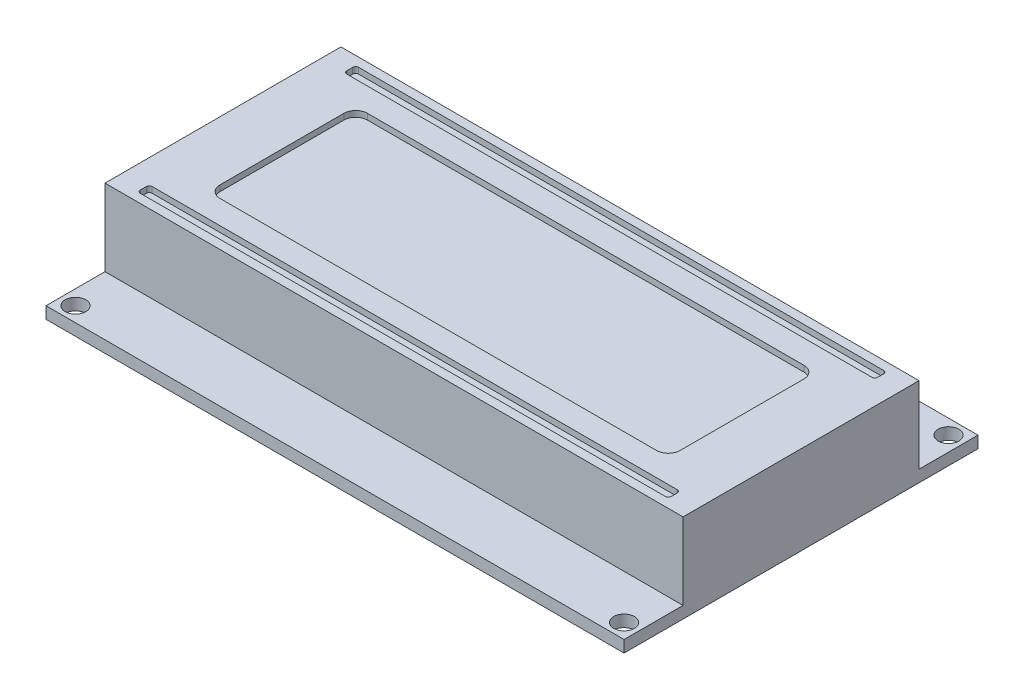
SolidWorks part; units mm, degrees
ref_plane "Front Plane" through (0, 0, 0) normal (0, 0, 1) x (1, 0, 0)
ref_plane "Top Plane" through (0, 0, 0) normal (0, 1, 0) x (1, 0, 0)
ref_plane "Right Plane" through (0, 0, 0) normal (1, 0, 0) x (0, 0, -1)
sketch "Sketch1" plane through (0, 0, 0) normal (0, 1, 0) x (1, 0, 0)
  line L0 (75, 55) -> (75, 0) construction
  line L1 (0, 0) -> (150, 0)
  line L2 (0, 0) -> (0, 55)
  line L3 (0, 55) -> (150, 55)
  line L4 (150, 0) -> (150, 55)
  line L5 (0, 27.5) -> (150, 27.5) construction
  circle A0 centre (3, 52) radius 1.5
  circle A1 centre (147, 52) radius 1.5
  circle A2 centre (147, 3) radius 1.5
  circle A3 centre (3, 3) radius 1.5
  dimension "D3" = 3
  dimension "D1" = 55
  dimension "D2" = 150
  dimension "D4" = 3
  dimension "D5" = 3
extrude "Boss-Extrude1" add sketch "Sketch1" along normal blind 2
sketch "Sketch2" plane through (0, 2, 0) normal (0, 1, 0) x (1, 0, 0)
  line L0 (0, 0) -> (150, 0) construction
  line L1 (0, 0) -> (0, 55) construction
  circle A0 centre (13, 10) radius 6
  dimension "D1" = 12
  dimension "D2" = 10
  dimension "D3" = 13
extrude "Boss-Extrude2" add sketch "Sketch2" along normal blind 10
sketch "Sketch3" plane through (0, 2, 0) normal (0, 1, 0) x (1, 0, 0)
  line L0 (0, 27.5) -> (150, 27.5) construction
  line L1 (7, 33.5) -> (19, 33.5)
  line L2 (7, 33.5) -> (7, 21.5)
  line L3 (7, 21.5) -> (19, 21.5)
  line L4 (19, 33.5) -> (19, 21.5)
  line L5 (13, 0) -> (13, 55) construction
  line L6 (0, 0) -> (150, 0) construction
  line L7 (0, 55) -> (150, 55) construction
  line L8 (7, 27.5) -> (19, 27.5) construction
  circle A1 centre (13, 10) radius 6 construction
  point P4 (7, 27.5)
  point P16 (13, 27.5)
  point P19 (13, 16)
  dimension "D1" = 12
  dimension "D2" = 12
extrude "Boss-Extrude3" add sketch "Sketch3" along normal blind 25
sketch "Sketch4" plane through (0, 2, 0) normal (0, 1, 0) x (1, 0, 0)
  line L0 (13, 45.5) -> (13, 40.5) construction
  line L1 (10.5, 45.5) -> (15.5, 45.5)
  line L2 (10.5, 45.5) -> (10.5, 40.5)
  line L3 (10.5, 40.5) -> (15.5, 40.5)
  line L4 (15.5, 45.5) -> (15.5, 40.5)
  line L5 (10.5, 43) -> (15.5, 43) construction
  line L7 (13, 0) -> (13, 55) construction
  line L8 (7, 33.5) -> (19, 33.5) construction
  line L9 (150, 0) -> (150, 55) construction
  line L10 (127, 8) -> (86, 8)
  line L11 (127, 8) -> (127, 5)
  line L12 (127, 5) -> (86, 5)
  line L13 (86, 8) -> (86, 5)
  line L14 (0, 0) -> (150, 0) construction
  point P8 (13, 43)
  dimension "D1" = 5
  dimension "D2" = 5
  dimension "D3" = 7
  dimension "D4" = 23
  dimension "D5" = 41
  dimension "D6" = 3
  dimension "D7" = 5
extrude "Boss-Extrude4" add sketch "Sketch4" along normal blind 5
sketch "Sketch5" plane through (0, 7, 0) normal (0, 1, 0) x (1, 0, 0)
  line L0 (86, 5) -> (127, 5) construction
  line L1 (86, 8) -> (127, 8)
  line L2 (86, 8) -> (86, 5)
  line L3 (86, 5) -> (127, 5)
  line L4 (127, 8) -> (127, 5)
  line L5 (86, 5) -> (127, 5) construction
  line L6 (10.5, 43) -> (15.5, 43) construction
  line L7 (10.5, 45.5) -> (10.5, 40.5) construction
  line L8 (15.5, 40.5) -> (15.5, 45.5) construction
  line L10 (10.5, 45.5) -> (15.5, 45.5)
  line L11 (10.5, 45.5) -> (10.5, 40.5)
  line L12 (10.5, 40.5) -> (15.5, 40.5)
  line L13 (15.5, 45.5) -> (15.5, 40.5)
  circle A0 centre (13, 43) radius 1.5
  point P15 (13, 43)
  dimension "D1" = 3
extrude "Cut-Extrude1" cut sketch "Sketch5" against normal blind 2
sketch "Sketch6" plane through (0, 27, 0) normal (0, 1, 0) x (1, 0, 0)
  line L0 (10.3706, 26.0556) -> (15.6294, 26.0556)
  line L1 (7, 33.5) -> (19, 33.5)
  line L2 (7, 33.5) -> (7, 21.5)
  line L3 (7, 21.5) -> (19, 21.5)
  line L4 (19, 33.5) -> (19, 21.5)
  arc A0 (15.6294, 26.0556) -> (10.3706, 26.0556) centre (13, 27.5) ccw
  dimension "D1" = 6
extrude "Cut-Extrude2" cut sketch "Sketch6" against normal blind 13
sketch "Sketch7" plane through (0, 14, 0) normal (0, 1, 0) x (1, 0, 0)
  line L1 (7, 33.5) -> (19, 33.5)
  line L2 (7, 33.5) -> (7, 21.5)
  line L3 (7, 21.5) -> (19, 21.5)
  line L4 (19, 33.5) -> (19, 21.5)
  circle A0 centre (13, 27.5) radius 3.5
  line M4 (7, 33.5) -> (7, 21.5)
  line M5 (7, 21.5) -> (19, 21.5)
  line M6 (19, 21.5) -> (19, 33.5)
  line M7 (19, 33.5) -> (7, 33.5)
  dimension "D1" = 7
extrude "Cut-Extrude3" cut sketch "Sketch7" against normal blind 7 contours A0 M7 M4 M5 M6
sketch "Sketch8" plane through (0, 12, 0) normal (0, 1, 0) x (1, 0, 0)
  circle A0 centre (13, 10) radius 1.25
  point P0 (13, 10)
  dimension "D1" = 2.5
extrude "Cut-Extrude4" cut sketch "Sketch8" against normal blind 5
sketch "Sketch9" plane through (0, 0, 0) normal (0, -1, 0) x (1, 0, 0)
  line L0 (0, -55) -> (150, -55) construction
  line L1 (149, -20) -> (131, -20)
  line L2 (149, -20) -> (149, -47)
  line L3 (149, -47) -> (124, -47)
  line L4 (124, -22) -> (124, -47)
  line L5 (150, 0) -> (150, -55) construction
  line L6 (124, -22) -> (129, -22)
  line L7 (129, -22) -> (131, -20)
  dimension "D1" = 8
  dimension "D2" = 27
  dimension "D3" = 1
  dimension "D4" = 25
  dimension "D5" = 2
  dimension "D6" = 5
  dimension "D7" = 45
extrude "Boss-Extrude5" add sketch "Sketch9" along normal blind 3
sketch "Sketch10" plane through (149, 0, 0) normal (1, 0, 0) x (0, 0, -1)
  line L0 (20, -1.5) -> (47, -1.5) construction
  line L1 (20, -3) -> (20, 0) construction
  line L2 (47, -3) -> (47, 0) construction
  line L3 (33.5, -3) -> (33.5, 0) construction
  line L4 (47, -3) -> (20, -3) construction
  line L5 (0, 0) -> (55, 0) construction
  line L6 (33.5, -2.25) -> (33.5, -0.75) construction
  line L7 (21, -2.25) -> (46, -2.25)
  line L8 (21, -2.25) -> (21, -0.75)
  line L9 (21, -0.75) -> (46, -0.75)
  line L10 (46, -2.25) -> (46, -0.75)
  line L11 (21, -1.5) -> (46, -1.5) construction
  point P20 (33.5, -1.5)
  point P21 (33.5, -1.5)
  dimension "D1" = 1.5
  dimension "D2" = 25
extrude "Cut-Extrude5" cut sketch "Sketch10" against normal blind 18
sketch "Sketch11" plane through (0, 5, 0) normal (0, 1, 0) x (1, 0, 0)
  line L0 (0, 0) -> (150, 0) construction
  line L1 (136, 64) -> (38, 64)
  line L2 (136, 64) -> (136, 4)
  line L3 (136, 4) -> (38, 4)
  line L4 (38, 64) -> (38, 4)
  line L5 (150, 0) -> (150, 55) construction
  line L6 (87, 64) -> (87, 4) construction
  line L7 (38, 34) -> (136, 34) construction
  circle A0 centre (40.5, 61.5) radius 1.75
  circle A1 centre (133.5, 61.5) radius 1.75
  circle A2 centre (133.5, 6.5) radius 1.75
  circle A3 centre (40.5, 6.5) radius 1.75
  point P12 (87, 34)
  dimension "D5" = 3.5
  dimension "D1" = 98
  dimension "D2" = 60
  dimension "D3" = 4
  dimension "D4" = 14
  dimension "D6" = 2.5
  dimension "D7" = 2.5
extrude "Boss-Extrude6" add sketch "Sketch11" along normal blind 2
sketch "Sketch12" plane through (0, 7, 0) normal (0, 1, 0) x (1, 0, 0)
  line L0 (38, 34) -> (136, 34) construction
  line L1 (38, 54) -> (136, 54)
  line L2 (38, 54) -> (38, 14)
  line L3 (38, 14) -> (136, 14)
  line L4 (136, 54) -> (136, 14)
  dimension "D1" = 40
extrude "Boss-Extrude7" add sketch "Sketch12" along normal blind 13
sketch "Sketch13" plane through (0, 20, 0) normal (0, 1, 0) x (1, 0, 0)
  line L0 (87, 54) -> (87, 14) construction
  line L1 (136, 54) -> (38, 54) construction
  line L2 (38, 14) -> (136, 14) construction
  line L3 (38, 34) -> (136, 34) construction
  line L4 (38, 54) -> (38, 14) construction
  line L5 (136, 14) -> (136, 54) construction
  line L6 (87, 46.5) -> (87, 21.5) construction
  line L7 (50, 46.5) -> (124, 46.5)
  line L8 (48, 44.5) -> (48, 23.5)
  line L9 (50, 21.5) -> (124, 21.5)
  line L10 (126, 44.5) -> (126, 23.5)
  line L11 (87, 52.5) -> (87, 50.5) construction
  line L12 (42.5, 52.5) -> (131.5, 52.5)
  line L13 (42, 52) -> (42, 51)
  line L14 (42.5, 50.5) -> (131.5, 50.5)
  line L15 (132, 52) -> (132, 51)
  line L16 (136, 54) -> (38, 54) construction
  line L17 (42, 52.5) -> (42, 50.5)
  line L18 (132, 52.5) -> (132, 50.5)
  line L19 (87, 15.5) -> (87, 17.5) construction
  line L20 (132, 16) -> (132, 17)
  line L21 (42, 16) -> (42, 17)
  line L22 (132, 15.5) -> (132, 17.5)
  line L23 (42.5, 17.5) -> (131.5, 17.5)
  line L24 (42, 15.5) -> (42, 17.5)
  line L25 (42.5, 15.5) -> (131.5, 15.5)
  arc A0 (131.5, 50.5) -> (132, 51) centre (131.5, 51) ccw
  arc A1 (131.5, 52.5) -> (132, 52) centre (131.5, 52) cw
  arc A2 (42, 51) -> (42.5, 50.5) centre (42.5, 51) ccw
  arc A3 (42.5, 52.5) -> (42, 52) centre (42.5, 52) ccw
  arc A4 (131.5, 15.5) -> (132, 16) centre (131.5, 16) ccw
  arc A5 (131.5, 17.5) -> (132, 17) centre (131.5, 17) cw
  arc A6 (42.5, 15.5) -> (42, 16) centre (42.5, 16) cw
  arc A7 (42.5, 17.5) -> (42, 17) centre (42.5, 17) ccw
  arc A8 (124, 46.5) -> (126, 44.5) centre (124, 44.5) cw
  arc A9 (48, 23.5) -> (50, 21.5) centre (50, 23.5) ccw
  arc A10 (50, 46.5) -> (48, 44.5) centre (50, 44.5) ccw
  arc A11 (124, 21.5) -> (126, 23.5) centre (124, 23.5) ccw
  point P18 (87, 34)
  point P19 (87, 34)
  point P62 (48, 21.5)
  point P65 (48, 46.5)
  dimension "D6" = 0.5
  dimension "D7" = 0.5
  dimension "D8" = 2
  dimension "D1" = 25
  dimension "D2" = 10
  dimension "D3" = 4
  dimension "D4" = 1.5
  dimension "D5" = 2
extrude "Cut-Extrude6" cut sketch "Sketch13" against normal blind 1 contours L15 L12 L13 L14 | L10 L7 L8 L9 | L21 L25 L20 L23
sketch "Sketch14" plane through (131, 0, 0) normal (1, 0, 0) x (0, 0, -1)
  line L1 (21, -0.75) -> (46, -0.75)
  line L2 (21, -0.75) -> (21, -2.25)
  line L3 (21, -2.25) -> (46, -2.25)
  line L4 (46, -0.75) -> (46, -2.25)
extrude "Boss-Extrude8" add sketch "Sketch14" along normal offset from surface (29 mm away) 11 up to face at (149, -1.5, -33.5) offset beyond the face yes
sketch "Sketch15" plane through (0, -3, 0) normal (0, -1, 0) x (1, 0, 0)
  line L0 (160, -46) -> (160, -21) construction
  line L1 (0, 0) -> (160, 0)
  line L2 (0, 0) -> (0, -64)
  line L3 (0, -64) -> (160, -64)
  line L4 (160, 0) -> (160, -64)
  line L5 (136, -64) -> (38, -64) construction
extrude "Cut-Extrude7" cut sketch "Sketch15" against normal up to vertex (8 mm away)
sketch "Sketch16" plane through (0, 5, 0) normal (0, -1, 0) x (1, 0, 0)
  line L1 (0, 0) -> (38, 0)
  line L2 (0, 0) -> (0, -64)
  line L3 (0, -64) -> (38, -64)
  line L4 (38, 0) -> (38, -64)
extrude "Cut-Extrude8" cut sketch "Sketch16" against normal through all
